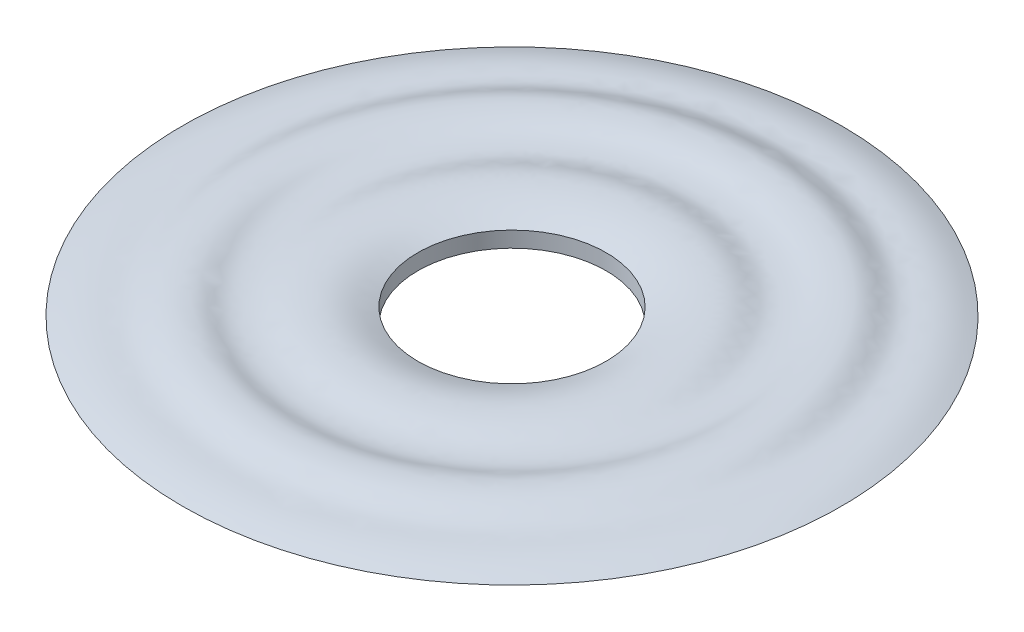
SolidWorks part; units mm, degrees
ref_plane "Front Plane" through (0, 0, 0) normal (0, 0, 1) x (1, 0, 0)
ref_plane "Top Plane" through (0, 0, 0) normal (0, 1, 0) x (1, 0, 0)
ref_plane "Right Plane" through (0, 0, 0) normal (1, 0, 0) x (0, 0, -1)
sketch "Sketch1" plane through (0, 0, 0) normal (0, 0, 1) x (1, 0, 0)
  line L0 (54, 7) -> (121.6363, 7) construction
  line L7 (0, 0) -> (134.2952, 0) construction
  line L8 (36, 3) -> (36, -3)
  spline S0 degree 3 poles (36, 3) (40.5852, 4.8077) (46.2816, 7.0534) (62.5042, 6.988) (65.8154, 3.8442) (80.6398, 4.1427) (81.4101, 6.9066) (97.6501, 7.1444) (100.7595, 2.7244) (116.6891, 3.2981) (121.7964, 1.489) (126, 0) knots 0 0 0 0 0.134921 0.167618 0.309257 0.350321 0.537199 0.581794 0.751672 0.795616 1 1 1 1
  spline S1 degree 3 poles (36, -3) (40.5852, -4.8077) (46.2816, -7.0534) (62.5042, -6.988) (65.8154, -3.8442) (80.6398, -4.1427) (81.4101, -6.9066) (97.6501, -7.1444) (100.7595, -2.7244) (116.6891, -3.2981) (121.7964, -1.489) (126, 0) knots 0 0 0 0 0.134921 0.167618 0.309257 0.350321 0.537199 0.581794 0.751672 0.795616 1 1 1 1
  dimension "D8" = 4
  dimension "D1" = 90
  dimension "D2" = 36
  dimension "D3" = 7
  dimension "D4" = 18
  dimension "D5" = 18
  dimension "D6" = 18
  dimension "D7" = 18
  dimension "D9" = 8
  dimension "D10" = 6
ref_axis "Axis1" through (0, 2.6159, 0) along (0, -1, 0)
revolve "Revolve1" add sketch "Sketch1" angle 360 about axis through (0, 2.6159, 0) along (0, -1, 0)
